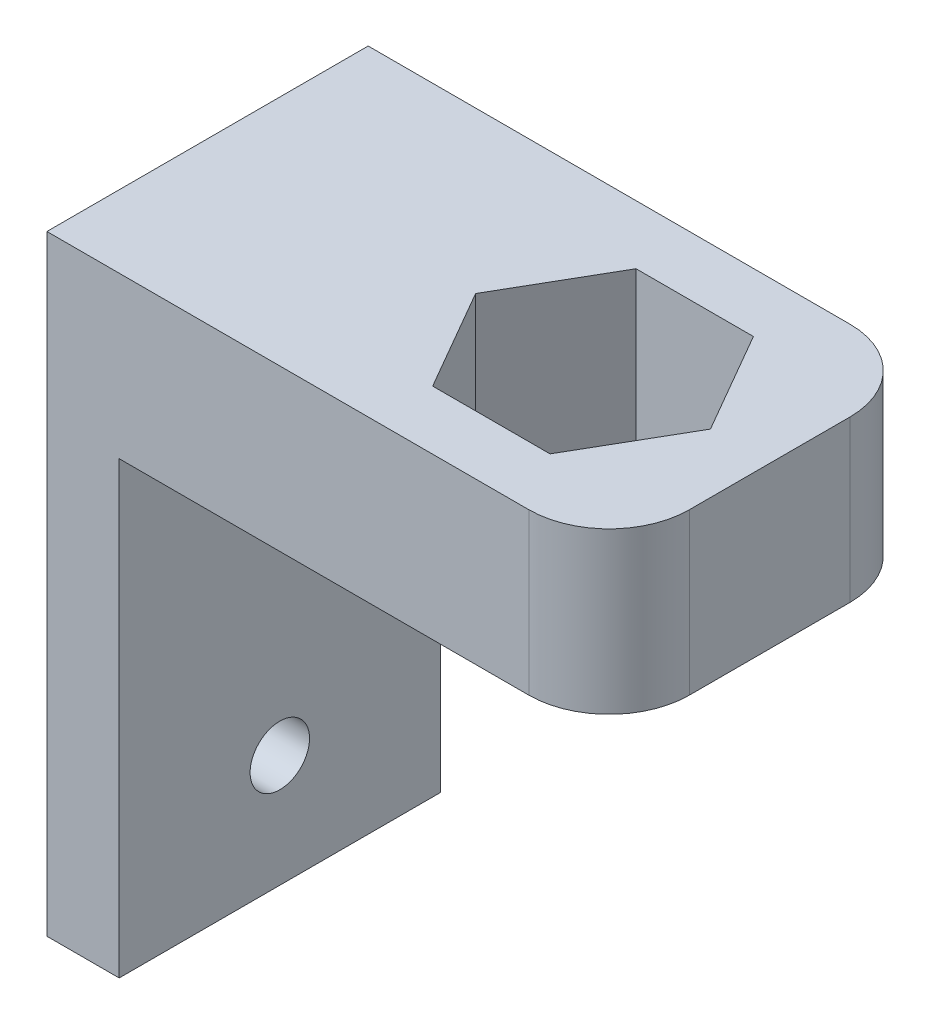
SolidWorks part; units mm, degrees
ref_plane "Front" through (0, 0, 0) normal (0, 0, 1) x (1, 0, 0)
ref_plane "Top" through (0, 0, 0) normal (0, 1, 0) x (1, 0, 0)
ref_plane "Right" through (0, 0, 0) normal (1, 0, 0) x (0, 0, -1)
sketch "Sketch1" plane through (0, 0, 0) normal (0, 1, 0) x (1, 0, 0)
  line L1 (-17.5, -10) -> (17.5, -10)
  line L2 (-17.5, -10) -> (-17.5, 10)
  line L3 (-17.5, 10) -> (17.5, 10)
  line L4 (17.5, -10) -> (17.5, 10)
  line L5 (-17.5, -10) -> (17.5, 10) construction
  line L6 (-17.5, 10) -> (17.5, -10) construction
  point P0 (0, 0)
  dimension "D2" = 20
  dimension "D3" = 35
extrude "Boss-Extrude1" add sketch "Sketch1" along normal blind 10
fillet "Fillet1" radius 5 2 edges at (17.5, 5, -10) (17.5, 5, 10)
sketch "Sketch4" plane through (0, 10, 0) normal (0, 1, 0) x (1, 0, 0)
  line L0 (17.5, -5) -> (17.5, 5) construction
  line L1 (-17.5, 0) -> (17.5, 0) construction
  line L2 (-17.5, 10) -> (-17.5, -10) construction
  line L3 (-17.5, -10) -> (12.5, -10) construction
  line L4 (10.1546, -6.33) -> (13.8093, 0)
  line L5 (13.8093, 0) -> (10.1546, 6.33)
  line L6 (10.1546, 6.33) -> (2.8454, 6.33)
  line L7 (2.8454, 6.33) -> (-0.8093, 0)
  line L8 (-0.8093, 0) -> (2.8454, -6.33)
  line L9 (2.8454, -6.33) -> (10.1546, -6.33)
  circle A1 centre (6.5, 0) radius 6.33 construction
  dimension "D1" = 12.66
  dimension "D2" = 24
extrude "Cut-Extrude2" cut sketch "Sketch4" against normal through all
sketch "Sketch5" plane through (0, 0, 0) normal (0, -1, 0) x (1, 0, 0)
  line L0 (12.5, -10) -> (-17.5, -10) construction
  line L1 (-17.5, 10) -> (-13, 10)
  line L2 (-17.5, 10) -> (-17.5, -10)
  line L3 (-17.5, -10) -> (-13, -10)
  line L4 (-13, 10) -> (-13, -10)
  dimension "D1" = 4.5
extrude "Boss-Extrude3" add sketch "Sketch5" along normal blind 28
sketch "Sketch6" plane through (-13, 0, 0) normal (1, 0, 0) x (0, 0, -1)
  line L0 (10, 0) -> (-10, 0) construction
  line L1 (0, -28) -> (0, 0) construction
  line L2 (10, -28) -> (-10, -28) construction
  circle A0 centre (0, -6) radius 1.85
  circle A1 centre (0, -6) radius 3.5 construction
  circle A2 centre (0, -21) radius 1.85
  circle A3 centre (0, -21) radius 3.5 construction
  dimension "D1" = 3.7
  dimension "D3" = 7
  dimension "D4" = 3.7
  dimension "D5" = 15
  dimension "D6" = 7
  dimension "D2" = 6
extrude "Cut-Extrude3" cut sketch "Sketch6" against normal through all
